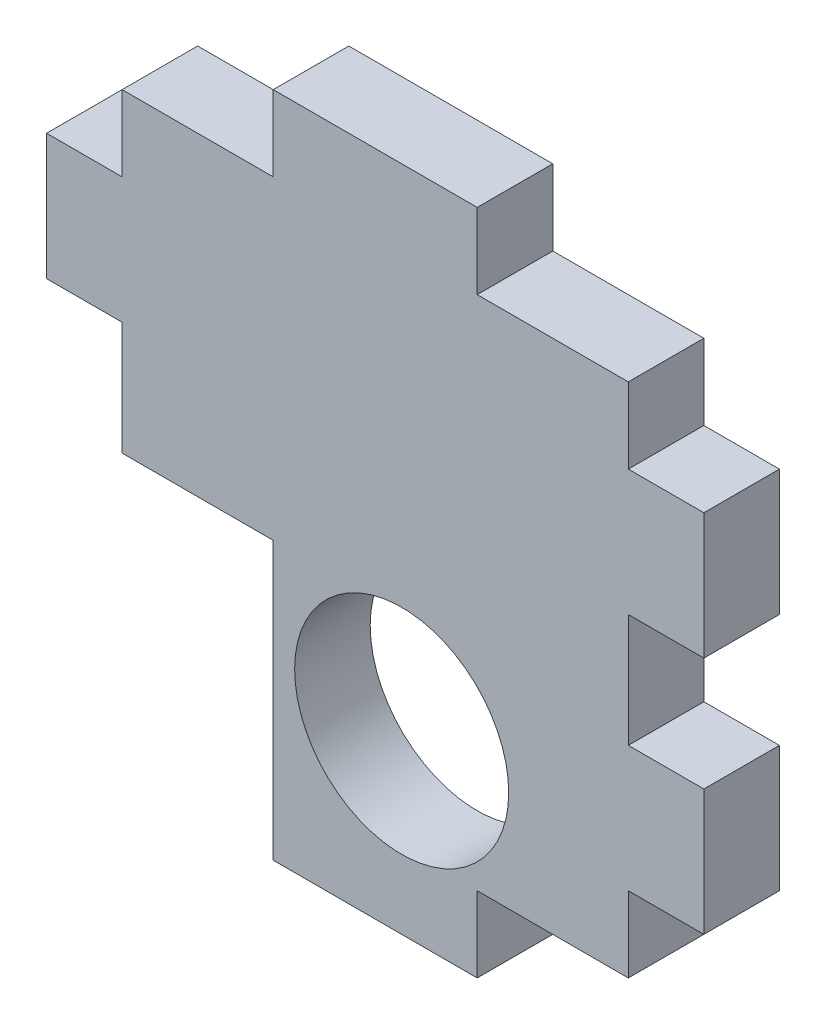
SolidWorks part; units mm, degrees
ref_plane "Plano frontal" through (0, 0, 0) normal (0, 0, 1) x (1, 0, 0)
ref_plane "Plano superior" through (0, 0, 0) normal (0, 1, 0) x (1, 0, 0)
ref_plane "Plano direito" through (0, 0, 0) normal (1, 0, 0) x (0, 0, -1)
sketch "BaseEsboco" plane through (0, 0, 0) normal (0, 0, 1) x (1, 0, 0)
  line L0 (0, 0) -> (6, 0)
  line L5 (6, 0) -> (6, -3)
  line L6 (6, -3) -> (14.1, -3)
  line L7 (14.1, -3) -> (14.1, 0)
  line L8 (14.1, 0) -> (20.1, 0)
  line L9 (20.1, 0) -> (20.1, 3)
  line L10 (20.1, 3) -> (23.1, 3)
  line L11 (23.1, 3) -> (23.1, 8)
  line L12 (23.1, 8) -> (20.1, 8)
  line L13 (20.1, 8) -> (20.1, 12.5)
  line L14 (20.1, 12.5) -> (23.1, 12.5)
  line L15 (23.1, 12.5) -> (23.1, 17.5)
  line L16 (23.1, 17.5) -> (20.1, 17.5)
  line L17 (20.1, 17.5) -> (20.1, 20.5)
  line L18 (20.1, 20.5) -> (14.1, 20.5)
  line L19 (14.1, 20.5) -> (14.1, 23.5)
  line L20 (14.1, 23.5) -> (6, 23.5)
  line L21 (6, 23.5) -> (6, 20.5)
  line L22 (6, 20.5) -> (0, 20.5)
  line L23 (0, 20.5) -> (0, 17.5)
  line L24 (0, 17.5) -> (-3, 17.5)
  line L25 (-3, 17.5) -> (-3, 12.5)
  line L26 (-3, 12.5) -> (0, 12.5)
  line L27 (0, 12.5) -> (0, 8)
  line L28 (0, 8) -> (-3, 8)
  line L29 (-3, 8) -> (-3, 3)
  line L30 (-3, 3) -> (0, 3)
  line L31 (0, 3) -> (0, 0)
  dimension "D1" = 26.5
  dimension "D2" = 26.1
  dimension "D3" = 9
  dimension "D4" = 9
  dimension "D5" = 6
  dimension "D6" = 5
  dimension "D7" = 6
  dimension "D8" = 5
  dimension "D9" = 3
  dimension "D10" = 3
  dimension "D11" = 3
  dimension "D12" = 3
extrude "Base" add sketch "BaseEsboco" along normal blind 3
sketch "Esboço1" plane through (0, 0, 3) normal (0, 0, 1) x (1, 0, 0)
  line L4 (0, 8) -> (6, 8)
  line L5 (6, 8) -> (6, 0)
  line L6 (6, 0) -> (0, 0)
  line L7 (0, 0) -> (0, 3)
  line L8 (0, 3) -> (-3, 3)
  line L9 (-3, 3) -> (-3, 8)
  line L10 (-3, 8) -> (0, 8)
  circle A0 centre (11.1, 4) radius 4.25
  point P21 (0, 0)
  dimension "D1" = 8.5
  dimension "D2" = 7
  dimension "D3" = 9
extrude "PassagemLEDeLDR" cut sketch "Esboço1" against normal blind 3
